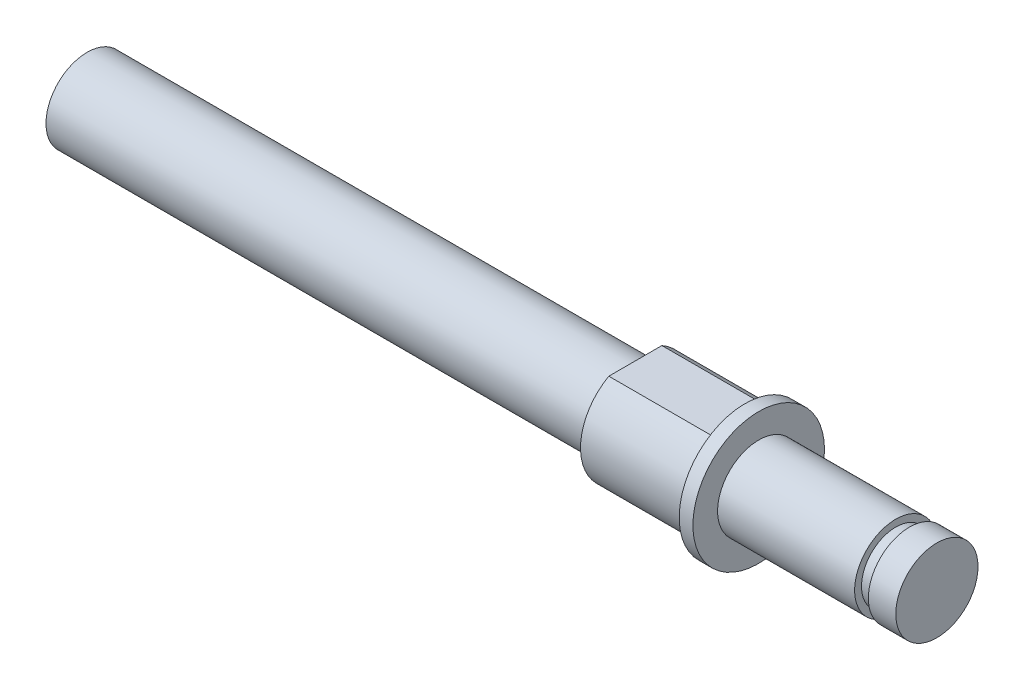
SolidWorks part; units mm, degrees
ref_plane "前视基准面" through (0, 0, 0) normal (0, 0, 1) x (1, 0, 0)
ref_plane "上视基准面" through (0, 0, 0) normal (0, 1, 0) x (1, 0, 0)
ref_plane "右视基准面" through (0, 0, 0) normal (1, 0, 0) x (0, 0, -1)
sketch "草图1" plane through (0, 0, 0) normal (1, 0, 0) x (0, 0, -1)
  circle A0 centre (0, 0) radius 1.5
extrude "凸台-拉伸1" add sketch "草图1" along normal blind 31
ref_plane "基准面1" through (20, 0, 0) normal (-1, 0, 0) x (0, 0, 1)
sketch "草图2" plane through (20, 0, 0) normal (-1, 0, 0) x (0, 0, 1)
  line L0 (0.9682, 1.75) -> (-0.9682, 1.75)
  arc A0 (-0.9682, 1.75) -> (0.9682, 1.75) centre (0, 0) ccw
  circle A1 centre (0, 0) radius 1.5
extrude "凸台-拉伸2" add sketch "草图2" against normal blind 4
sketch "草图3" plane through (24, 0, 0) normal (1, 0, 0) x (0, 0, -1)
  circle A0 centre (0, 0) radius 1.5
  circle A1 centre (0, 0) radius 2.4
extrude "凸台-拉伸3" add sketch "草图3" along normal blind 0.5
sketch "草图4" plane through (31, 0, 0) normal (1, 0, 0) x (0, 0, -1)
  circle A0 centre (0, 0) radius 1.25
  circle A1 centre (0, 0) radius 1.5
extrude "切除-拉伸1" cut sketch "草图4" against normal blind 0.5 from offset 1
